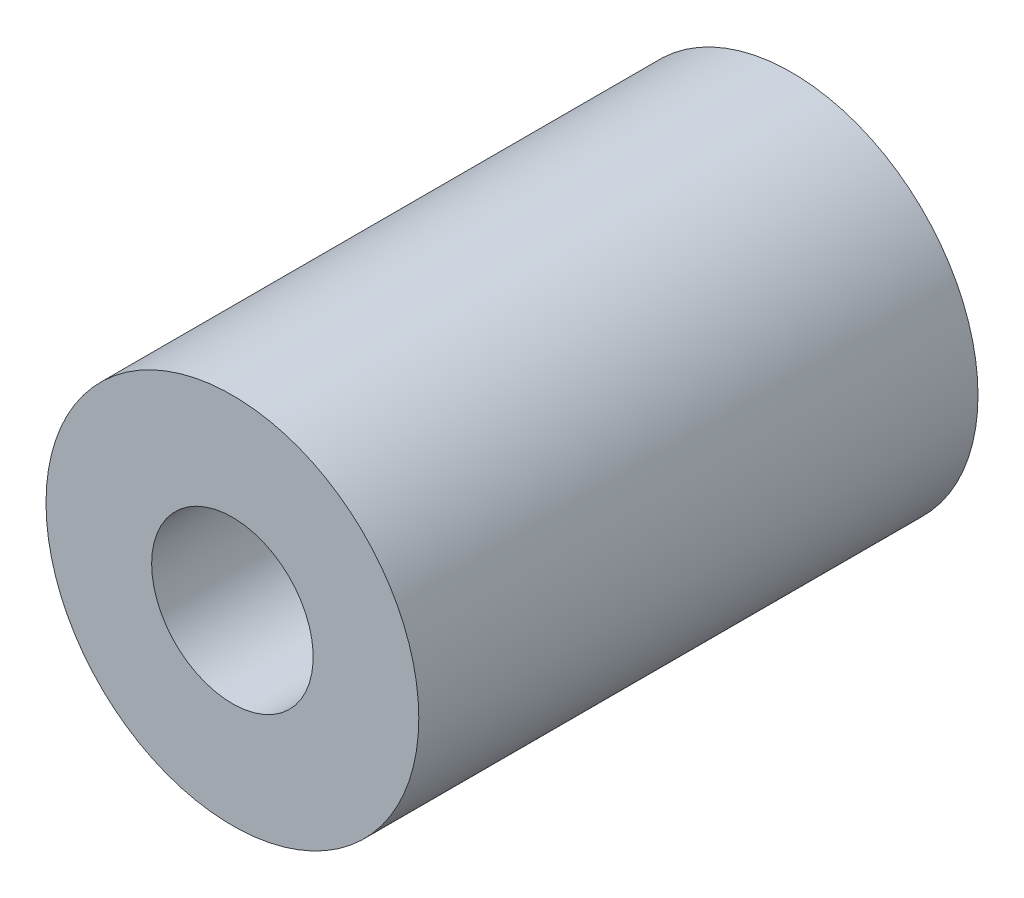
SolidWorks part; units mm, degrees
material "黄铜"
ref_plane "前视基准面" through (0, 0, 0) normal (0, 0, 1) x (1, 0, 0)
ref_plane "上视基准面" through (0, 0, 0) normal (0, 1, 0) x (1, 0, 0)
ref_plane "右视基准面" through (0, 0, 0) normal (1, 0, 0) x (0, 0, -1)
sketch "草图1" plane through (0, 0, 0) normal (0, 0, 1) x (1, 0, 0)
  circle A0 centre (0, 0) radius 6.5
  circle A1 centre (0, 0) radius 15
  dimension "D1" = 13
  dimension "D2" = 30
extrude "拉伸1" add sketch "草图1" along normal mid plane 45
